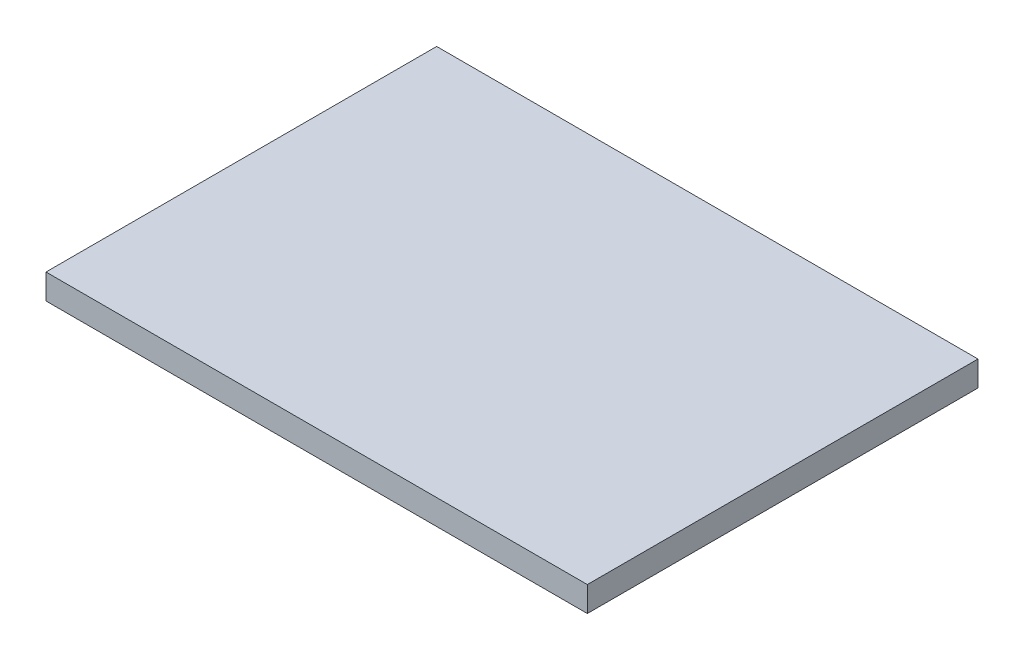
SolidWorks part; units mm, degrees
ref_plane "前视基准面" through (0, 0, 0) normal (0, 0, 1) x (1, 0, 0)
ref_plane "上视基准面" through (0, 0, 0) normal (0, 1, 0) x (1, 0, 0)
ref_plane "右视基准面" through (0, 0, 0) normal (1, 0, 0) x (0, 0, -1)
sketch "草图1" plane through (0, 0, 0) normal (0, 1, 0) x (1, 0, 0)
  line L1 (0, 0) -> (388, 0)
  line L2 (0, 0) -> (0, -280)
  line L3 (0, -280) -> (388, -280)
  line L4 (388, 0) -> (388, -280)
  dimension "D1" = 388
  dimension "D2" = 280
extrude "凸台-拉伸1" add sketch "草图1" along normal blind 18
